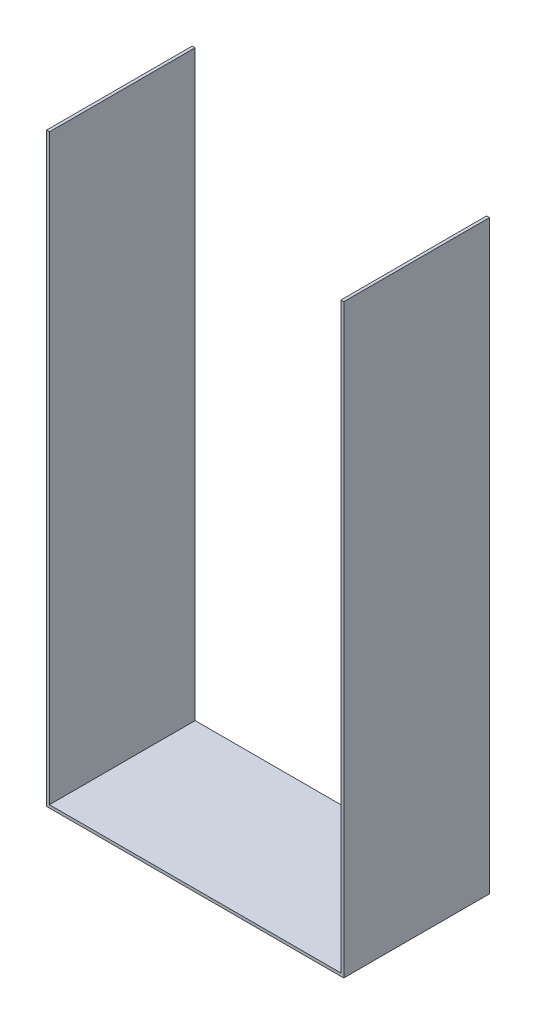
SolidWorks part; units mm, degrees
ref_plane "Front Plane" through (0, 0, 0) normal (0, 0, 1) x (1, 0, 0)
ref_plane "Top Plane" through (0, 0, 0) normal (0, 1, 0) x (1, 0, 0)
ref_plane "Right Plane" through (0, 0, 0) normal (1, 0, 0) x (0, 0, -1)
sketch "Sketch2" plane through (0, 0, 0) normal (0, 0, 1) x (1, 0, 0)
  line L0 (0, 0) -> (0, -40000)
  line L1 (0, -40000) -> (20000, -40000)
  line L2 (20000, -40000) -> (20000, 0)
  line L3 (-200, 0) -> (-200, -40200)
  line L4 (-200, -40200) -> (20200, -40200)
  line L5 (20200, -40200) -> (20200, 0)
  line L6 (-200, 0) -> (0, 0)
  line L7 (20000, 0) -> (20200, 0)
extrude "Boss-Extrude1" add sketch "Sketch2" against normal blind 10000
